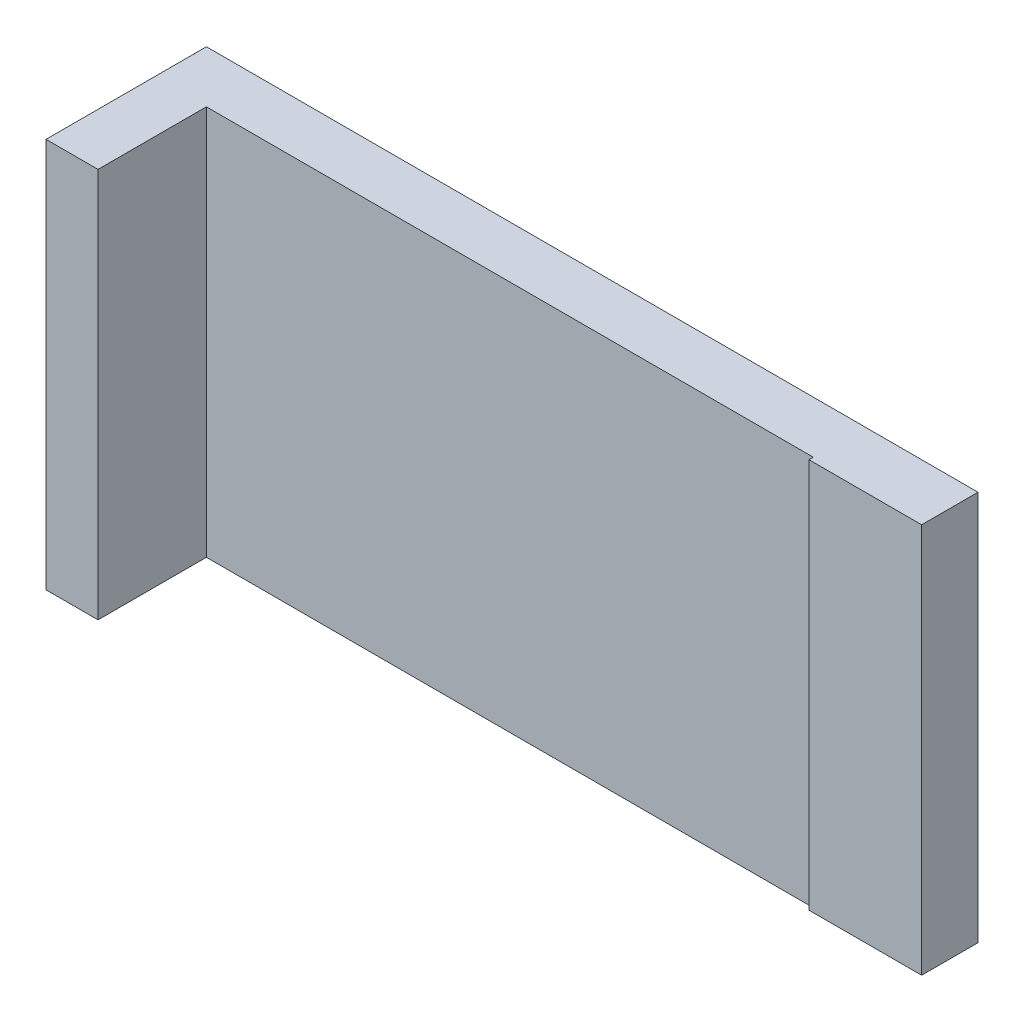
SolidWorks part; units mm, degrees
ref_plane "Plano frontal" through (0, 0, 0) normal (0, 0, 1) x (1, 0, 0)
ref_plane "Plano superior" through (0, 0, 0) normal (0, 1, 0) x (1, 0, 0)
ref_plane "Plano direito" through (0, 0, 0) normal (1, 0, 0) x (0, 0, -1)
other "Centro da massa"
sketch "Esboço1" plane through (0, 0, 0) normal (0, 0, 1) x (1, 0, 0)
  line L0 (-16, 3.25) -> (-16, -3.25) construction
  line L1 (-16.25, -11.25) -> (25.25, -11.25)
  line L2 (-16.25, -11.25) -> (-16.25, 11.25)
  line L3 (-16.25, 11.25) -> (25.25, 11.25)
  line L4 (25.25, -11.25) -> (25.25, 11.25)
  line L6 (22, -8) -> (22, -11.25) construction
  line L7 (22, -8) -> (25.25, -8) construction
  line L9 (22, 8) -> (22, 11.25) construction
  line L11 (25.5, -8.2779) -> (25.5, 29.7721) construction
  dimension "D1" = 0.25
  dimension "D2" = 0.25
extrude "Ressalto-extrusão1" add sketch "Esboço1" against normal blind 3
sketch "Esboço2" plane through (-16.25, 0, 0) normal (-1, 0, 0) x (0, 0, 1)
  line L1 (-3, -11.25) -> (6.25, -11.25)
  line L2 (-3, -11.25) -> (-3, 11.25)
  line L3 (-3, 11.25) -> (6.25, 11.25)
  line L4 (6.25, -11.25) -> (6.25, 11.25)
  line L5 (6.5, 29.8) -> (6.5, 13.8) construction
  line L6 (-3, 11.25) -> (0, 11.25) construction
  dimension "D1" = 0.25
extrude "Ressalto-extrusão2" add sketch "Esboço2" along normal blind 3
sketch "Esboço3" plane through (0, 0, -3) normal (0, 0, 1) x (1, 0, 0)
  line L0 (25.25, 11.25) -> (-16.25, 11.25) construction
  line L1 (25.25, -11.25) -> (18.75, -11.25)
  line L2 (25.25, -11.25) -> (25.25, 11.25)
  line L3 (25.25, 11.25) -> (18.75, 11.25)
  line L4 (18.75, -11.25) -> (18.75, 11.25)
  line L5 (18.75, 16) -> (25.25, 16) construction
  circle A0 centre (22, 16) radius 1.25 construction
  point P9 (22, 16)
extrude "Ressalto-extrusão3" add sketch "Esboço3" along normal offset from surface (3.25 mm away) 0.25
move or copy body "Corpo-Mover/Copiar1" [suppressed] bodies to move or copy 102 103
